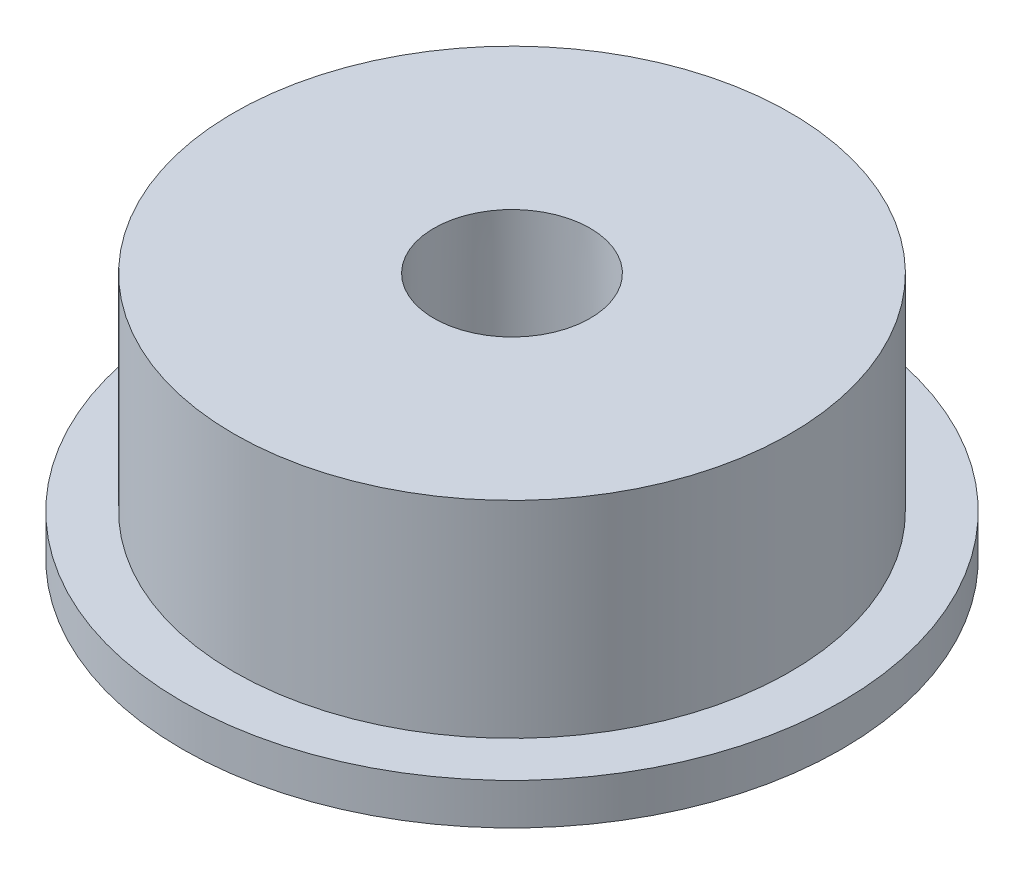
SolidWorks part; units mm, degrees
material "ABS"
ref_plane "Front Plane" through (0, 0, 0) normal (0, 0, 1) x (1, 0, 0)
ref_plane "Top Plane" through (0, 0, 0) normal (0, 1, 0) x (1, 0, 0)
ref_plane "Right Plane" through (0, 0, 0) normal (1, 0, 0) x (0, 0, -1)
sketch "Sketch1" plane through (0, 0, 0) normal (0, 1, 0) x (1, 0, 0)
  circle A0 centre (0, 0) radius 8
  dimension "D1" = 16
extrude "Boss-Extrude1" add sketch "Sketch1" along normal blind 1
sketch "Sketch2" plane through (0, 1, 0) normal (0, 1, 0) x (1, 0, 0)
  circle A0 centre (0, 0) radius 6.75
  dimension "D1" = 13.5
extrude "Boss-Extrude2" add sketch "Sketch2" along normal blind 5
sketch "Sketch3" plane through (0, 0, 0) normal (0, -1, 0) x (1, 0, 0)
  circle A0 centre (0, 0) radius 2
  dimension "D1" = 4
extrude "Cut-Extrude1" cut sketch "Sketch3" against normal through all draft 1
